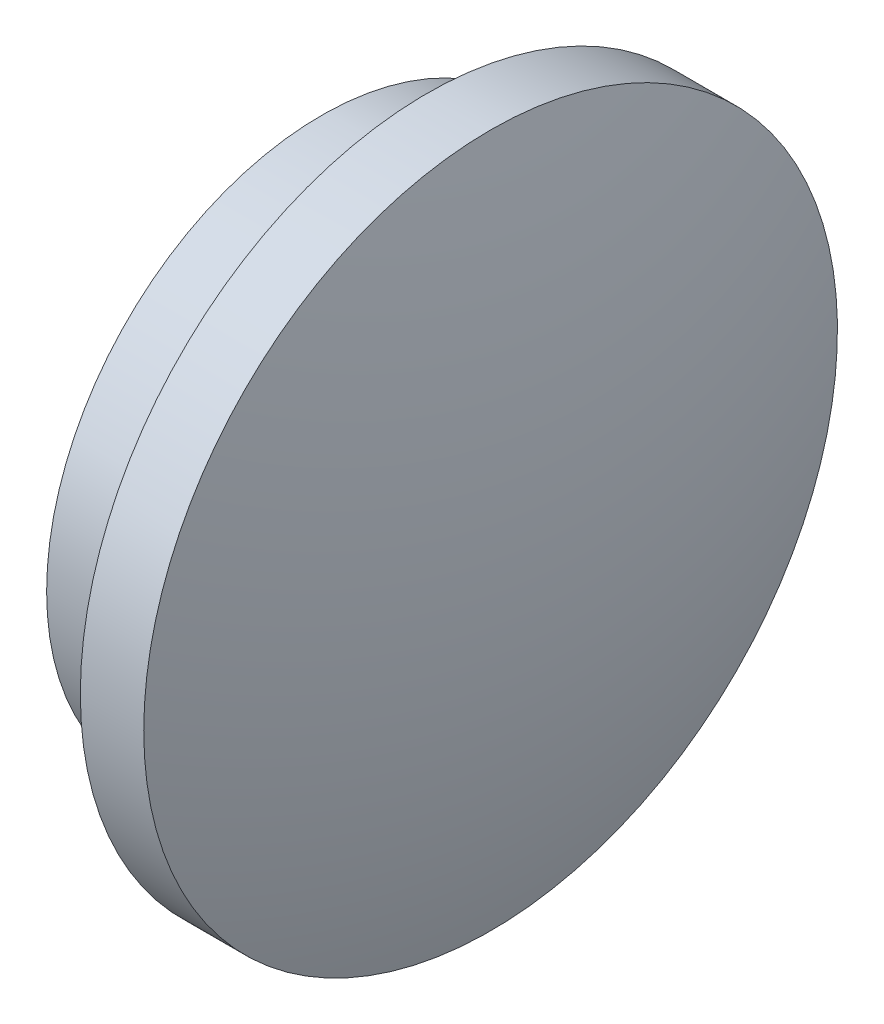
SolidWorks part; units mm, degrees
material "Plain Carbon Steel"
ref_plane "Front Plane" through (0, 0, 0) normal (0, 0, 1) x (1, 0, 0)
ref_plane "Top Plane" through (0, 0, 0) normal (0, 1, 0) x (1, 0, 0)
ref_plane "Right Plane" through (0, 0, 0) normal (1, 0, 0) x (0, 0, -1)
sketch "Sketch1" plane through (0, 0, 0) normal (0, 0, 1) x (1, 0, 0)
  line L0 (-44.9215, 0) -> (58.2618, 0) construction
  line L1 (-12.5778, 0) -> (-12.5778, 26)
  line L2 (-12.5778, 26) -> (-2.5778, 26)
  line L3 (-2.5778, 26) -> (-2.5778, 32.8127)
  line L4 (-2.5778, 32.8127) -> (3.4222, 32.8127)
  line L5 (-12.5778, 0) -> (8.6408, 0)
  arc A0 (3.4222, 32.8127) -> (8.6408, 0) centre (-97.1265, 0) cw
  point P12 (0, 0)
  dimension "D1" = 26
  dimension "D2" = 10
  dimension "D4" = 6
revolve "Revolve1" add sketch "Sketch1" angle 360 about L0
